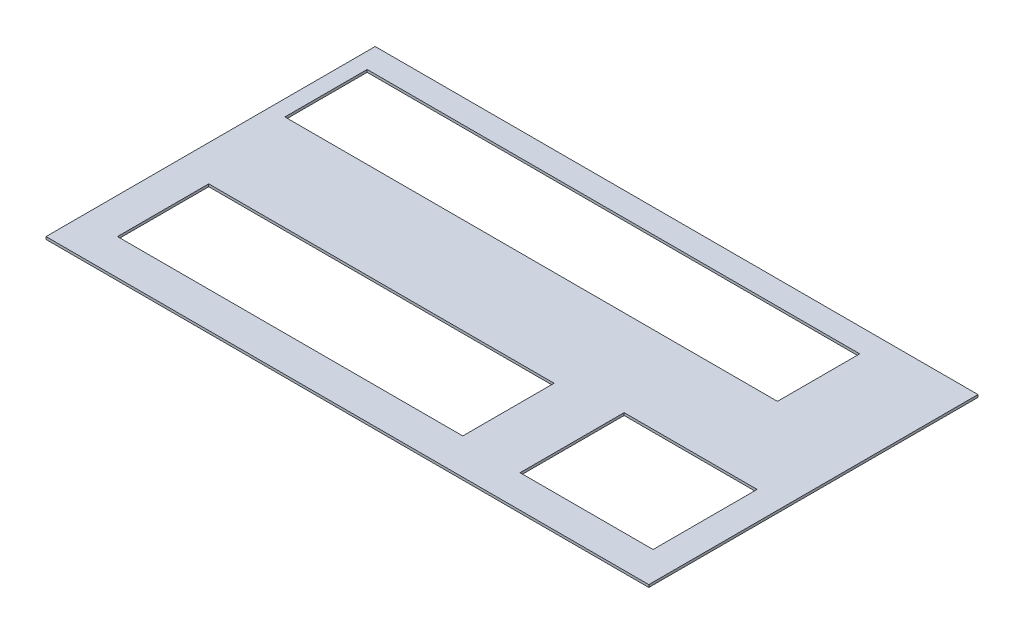
SolidWorks part; units mm, degrees
material "Particle Board"
ref_plane "Front Plane" through (0, 0, 0) normal (0, 0, 1) x (1, 0, 0)
ref_plane "Top Plane" through (0, 0, 0) normal (0, 1, 0) x (1, 0, 0)
ref_plane "Right Plane" through (0, 0, 0) normal (1, 0, 0) x (0, 0, -1)
sketch "Sketch1" plane through (0, 0, 0) normal (0, 1, 0) x (1, 0, 0)
  line L1 (0, 0) -> (1518.68, 0)
  line L2 (0, 0) -> (0, 829.31)
  line L3 (0, 829.31) -> (1518.68, 829.31)
  line L4 (1518.68, 0) -> (1518.68, 829.31)
  dimension "D1" = 1518.68
  dimension "D2" = 829.31
extrude "Boss-Extrude1" add sketch "Sketch1" along normal blind 6.35
sketch "Sketch2" plane through (0, 6.35, 0) normal (0, 1, 0) x (1, 0, 0)
  line L0 (0, 829.31) -> (0, 0) construction
  line L1 (90, 90) -> (960, 90)
  line L2 (90, 90) -> (90, 320)
  line L3 (90, 320) -> (960, 320)
  line L4 (960, 90) -> (960, 320)
  line L5 (0, 0) -> (1518.68, 0) construction
  line L7 (39.9459, 769.1459) -> (1280.9007, 769.1459)
  line L8 (39.9459, 769.1459) -> (39.9459, 561.8468)
  line L9 (39.9459, 561.8468) -> (1280.9007, 561.8468)
  line L10 (1280.9007, 769.1459) -> (1280.9007, 561.8468)
  line L11 (1447.4973, 344.1354) -> (1112.4111, 344.1354)
  line L12 (1447.4973, 344.1354) -> (1447.4973, 81.9352)
  line L13 (1447.4973, 81.9352) -> (1112.4111, 81.9352)
  line L14 (1112.4111, 344.1354) -> (1112.4111, 81.9352)
  dimension "D1" = 870
  dimension "D2" = 230
  dimension "D3" = 90
  dimension "D4" = 90
extrude "Cut-Extrude1" cut sketch "Sketch2" against normal up to next
